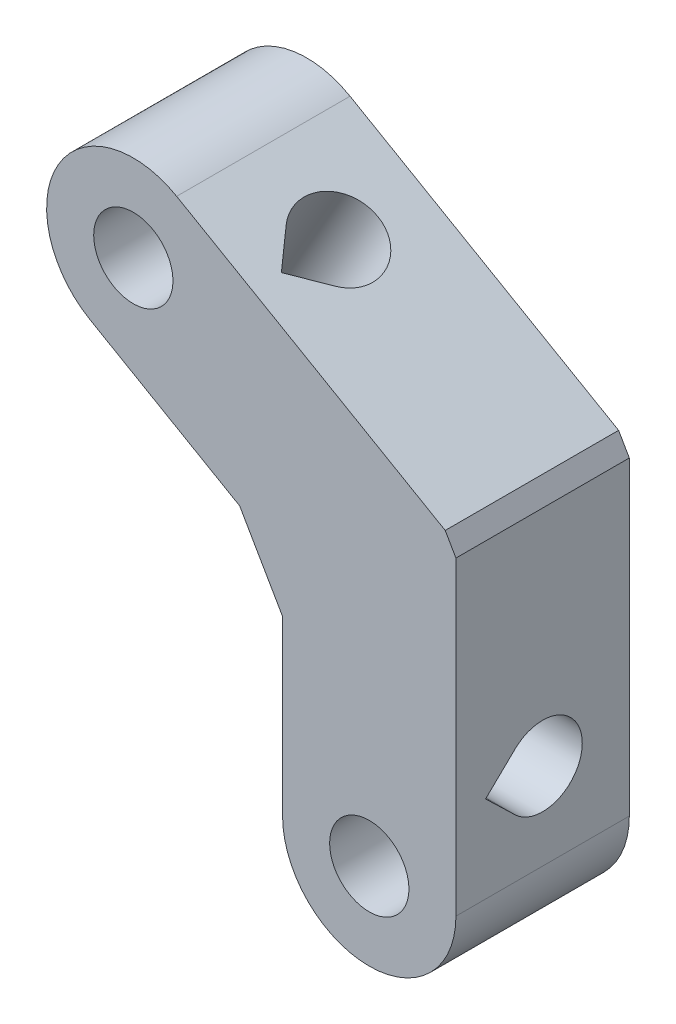
SolidWorks part; units mm, degrees
ref_plane "Front Plane" through (0, 0, 0) normal (0, 0, 1) x (1, 0, 0)
ref_plane "Top Plane" through (0, 0, 0) normal (0, 1, 0) x (1, 0, 0)
ref_plane "Right Plane" through (0, 0, 0) normal (1, 0, 0) x (0, 0, -1)
ref_plane "Plane4" through (0, 0, 14) normal (0, 0, 1) x (1, 0, 0)
sketch "Sketch1" plane through (0, 0, 14) normal (0, 0, 1) x (1, 0, 0)
  line L0 (7, 0) -> (7, 25.0415)
  line L1 (7, 25.0415) -> (6.134, 26.5415)
  line L2 (6.134, 26.5415) -> (-15.5526, 39.0622)
  line L3 (-22.5526, 26.9378) -> (-10.4641, 19.9585)
  line L4 (-10.4641, 19.9585) -> (-7, 13.9585)
  line L5 (-7, 13.9585) -> (-7, 0)
  arc A0 (-15.5526, 39.0622) -> (-22.5526, 26.9378) centre (-19.0526, 33) ccw
  arc A1 (-7, 0) -> (7, 0) centre (0, 0) ccw
extrude "Boss-Extrude1" add sketch "Sketch1" against normal blind 14
sketch "Sketch2" plane through (6.0263, 10.4378, 0) normal (-0.5, -0.866, 0) x (0.866, -0.5, 0)
  line L0 (-26, 11.6066) -> (-28.3019, 9.2229)
  line L1 (-23.6981, 9.2229) -> (-26, 11.6066)
  arc A0 (-28.3019, 9.2229) -> (-23.6981, 9.2229) centre (-26, 7) ccw
extrude "Cut-Extrude1" cut sketch "Sketch2" against normal through all
sketch "Sketch3" plane through (-7, 0, 0) normal (-1, 0, 0) x (0, 0, 1)
  line L0 (9.2229, 4.6981) -> (11.6066, 7)
  line L1 (11.6066, 7) -> (9.2229, 9.3019)
  arc A0 (9.2229, 9.3019) -> (9.2229, 4.6981) centre (7, 7) ccw
extrude "Cut-Extrude2" cut sketch "Sketch3" against normal through all
hole_wizard "Hole1" positions "Sketch5" profile "Sketch4" legacy
sketch "Sketch5" plane through (0, 0, 0) normal (0, 0, -1) x (-1, 0, 0)
  point P0 (0, 0)
sketch "Sketch4" plane through (0, 0, 0) normal (1, 0, 0) x (0, 1, 0)
  line L0 (0, 0) -> (0, 14)
  line L1 (0, 14) -> (3.2, 14)
  line L2 (3.2, 14) -> (3.2, 0)
  line L3 (3.2, 0) -> (0, 0)
  line L4 (0, 110) -> (0, -10) construction
  dimension "Diameter" = 6.4
  dimension "Depth" = 14
hole_wizard "Hole2" positions "Sketch7" profile "Sketch6" legacy
sketch "Sketch7" plane through (0, 0, 0) normal (0, 0, -1) x (-1, 0, 0)
  line L0 (0, 0) -> (19.0525, 32.9999) construction
  line L2 (0, 0) -> (22.3725, 0) construction
  point P0 (19.0525, 32.9999)
  dimension "D1" = 38.105
  dimension "D2" = 60
sketch "Sketch6" plane through (-19.0525, 32.9999, 0) normal (1, 0, 0) x (0, 1, 0)
  line L0 (0, 0) -> (0, 14)
  line L1 (0, 14) -> (3.2, 14)
  line L2 (3.2, 14) -> (3.2, 0)
  line L3 (3.2, 0) -> (0, 0)
  line L4 (0, 110) -> (0, -10) construction
  dimension "Diameter" = 6.4
  dimension "Depth" = 14
